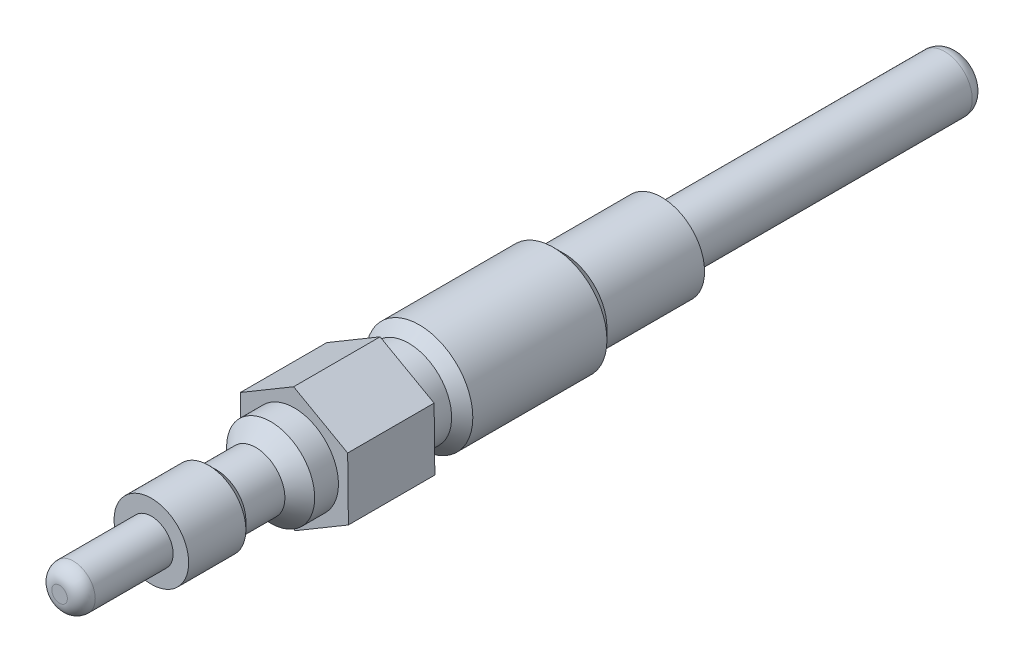
SolidWorks part; units mm, degrees
ref_plane "Front Plane" through (0, 0, 0) normal (0, 0, 1) x (1, 0, 0)
ref_plane "Top Plane" through (0, 0, 0) normal (0, 1, 0) x (1, 0, 0)
ref_plane "Right Plane" through (0, 0, 0) normal (1, 0, 0) x (0, 0, -1)
ref_axis "Axis1" through (0, 0, -56.7233) along (0, 0, 1)
sketch "Sketch1" plane through (0, 0, 0) normal (0, 0, 1) x (1, 0, 0)
  line L1 (4.8553, 2.8814) -> (-0.0677, 5.6455)
  line L2 (-0.0677, 5.6455) -> (-4.923, 2.7641)
  line L3 (-4.923, 2.7641) -> (-4.8553, -2.8814)
  line L4 (-4.8553, -2.8814) -> (0.0677, -5.6455)
  line L5 (0.0677, -5.6455) -> (4.923, -2.7641)
  line L6 (4.923, -2.7641) -> (4.8553, 2.8814)
  circle A0 centre (0, 0) radius 4.8895 construction
extrude "Boss-Extrude1" add sketch "Sketch1" along normal blind 7.874
sketch "Sketch2" plane through (0, 0, 7.874) normal (0, 0, 1) x (1, 0, 0)
  circle A0 centre (0, 0) radius 4.0132
extrude "Boss-Extrude2" add sketch "Sketch2" along normal blind 21.3868 contours A0
sketch "Sketch3" plane through (0, 0, 0) normal (0, 0, -1) x (-1, 0, 0)
  circle A0 centre (0, 0) radius 4.8768
extrude "Boss-Extrude3" add sketch "Sketch3" along normal blind 52.6288
sketch "Sketch8" plane through (0, 0, 0) normal (1, 0, 0) x (0, 0, -1)
  line L0 (0, 3.9116) -> (2.54, 3.9116)
  line L1 (0, -4.8768) -> (0, 4.8768) construction
  line L2 (2.54, 3.9116) -> (4.8963, 6.2679)
  line L3 (4.8963, 6.2679) -> (4.8963, 7.7216)
  line L4 (4.8963, 7.7216) -> (0, 7.7216)
  line L5 (0, 7.7216) -> (0, 3.9116)
  line L6 (5.4153, 0) -> (-5.4153, 0) construction
  dimension "D1" = 45
  dimension "D2" = 3.9116
  dimension "D3" = 2.54
  dimension "D4" = 3.81
revolve "Cut-Revolve1" cut sketch "Sketch8" angle 360 about axis through (0, 0, -56.7233) along (0, 0, 1)
sketch "Sketch9" plane through (0, 0, 0) normal (1, 0, 0) x (0, 0, -1)
  line L0 (16.6878, 3.9116) -> (14.8707, 5.7287)
  line L1 (14.8707, 5.7287) -> (14.8707, 7.7216)
  line L2 (14.8707, 7.7216) -> (25.5778, 7.7216)
  line L3 (25.5778, 7.7216) -> (25.5778, 3.9116)
  line L4 (25.5778, 3.9116) -> (16.6878, 3.9116)
  line L5 (56.7233, 0) -> (-33.3553, 0) construction
  dimension "D1" = 14.1478
  dimension "D2" = 8.89
  dimension "D3" = 45
  dimension "D4" = 3.81
revolve "Cut-Revolve2" cut sketch "Sketch9" angle 360 about axis through (0, 0, -56.7233) along (0, 0, 1)
sketch "Sketch10" plane through (0, 0, 0) normal (1, 0, 0) x (0, 0, -1)
  line L0 (25.5778, 3.9116) -> (25.5778, -3.9116) construction
  line L1 (25.5778, 2.5146) -> (56.0578, 2.5146)
  line L2 (25.5778, 2.5146) -> (25.5778, 6.3246)
  line L3 (25.5778, 6.3246) -> (56.0578, 6.3246)
  line L4 (56.0578, 2.5146) -> (56.0578, 6.3246)
  line L5 (56.7233, 0) -> (-33.3553, 0) construction
  dimension "D1" = 30.48
  dimension "D2" = 3.81
  dimension "D3" = 2.5146
revolve "Cut-Revolve3" cut sketch "Sketch10" angle 360 about axis through (0, 0, -56.7233) along (0, 0, 1)
fillet "Fillet1" radius 1.27 1 edges at (-2.5146, 0, -52.6288)
sketch "Sketch13" plane through (0, 0, 0) normal (1, 0, 0) x (0, 0, -1)
  line L0 (-10.033, 4.0132) -> (-11.3919, 2.6543)
  line L1 (-7.874, 4.0132) -> (-29.2608, 4.0132) construction
  line L2 (-11.3919, 2.6543) -> (-14.9479, 2.6543)
  line L3 (-14.9479, 2.6543) -> (-15.6917, 3.3981)
  line L4 (-15.6917, 3.3981) -> (-20.8987, 3.3981)
  line L5 (-20.8987, 3.3981) -> (-20.8987, 1.9812)
  line L6 (-20.8987, 1.9812) -> (-29.2608, 1.9812)
  line L7 (-29.2608, 4.0132) -> (-29.2608, -4.0132) construction
  line L8 (-29.2608, 1.9812) -> (-29.2608, 6.5149)
  line L9 (-29.2608, 6.5149) -> (-10.033, 6.5149)
  line L10 (-10.033, 6.5149) -> (-10.033, 4.0132)
  line L11 (-7.874, 2.8814) -> (-7.874, 5.6455) construction
  line L12 (56.7233, 0) -> (-33.3553, 0) construction
  dimension "D1" = 2.159
  dimension "D2" = 45
  dimension "D3" = 2.6543
  dimension "D4" = 45
  dimension "D5" = 3.556
  dimension "D6" = 5.207
  dimension "D7" = 1.9812
revolve "Cut-Revolve4" cut sketch "Sketch13" angle 360 about axis through (0, 0, -56.7233) along (0, 0, 1)
fillet "Fillet2" radius 1.27 1 edges at (-1.9812, 0, 29.2608)
